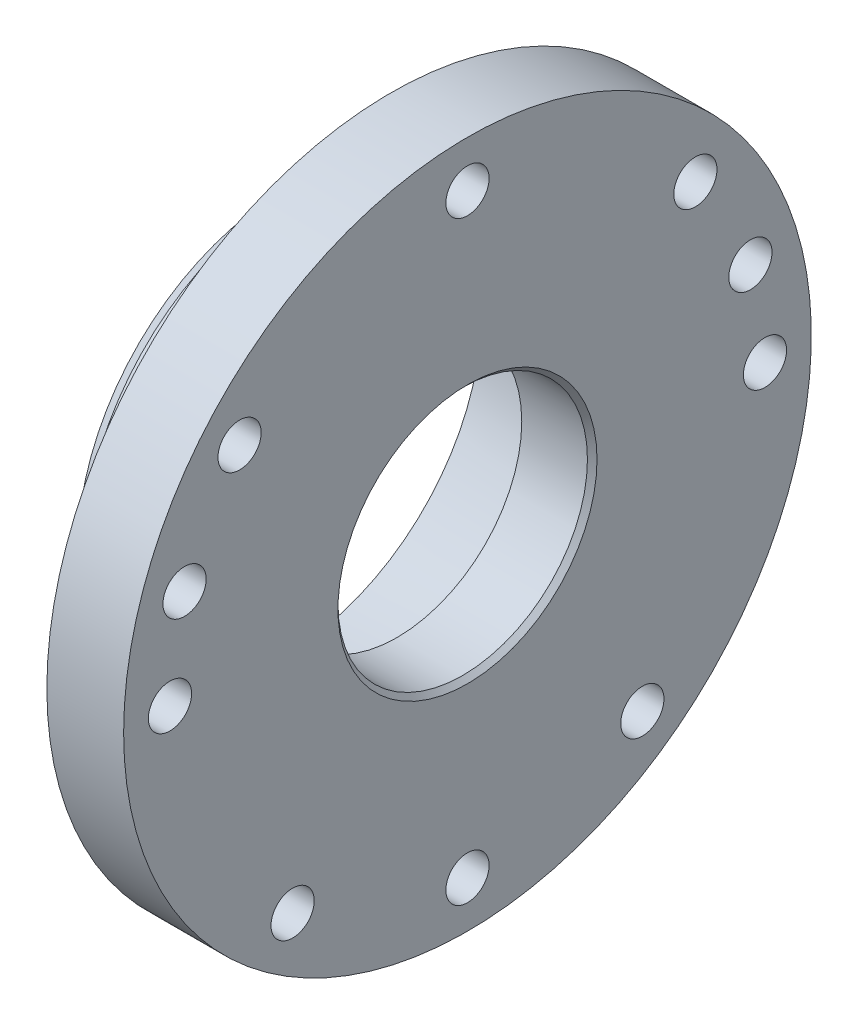
SolidWorks part; units mm, degrees
material "CD4Mc-U Duplex Stainless Steel"
ref_plane "Front Plane" through (0, 0, 0) normal (0, 0, 1) x (1, 0, 0)
ref_plane "Top Plane" through (0, 0, 0) normal (0, 1, 0) x (1, 0, 0)
ref_plane "Right Plane" through (0, 0, 0) normal (1, 0, 0) x (0, 0, -1)
sketch "Sketch1" plane through (0, 0, 0) normal (0, 0, 1) x (1, 0, 0)
  line L0 (0, 0) -> (170.4703, 0) construction
  line L1 (0, 65.0875) -> (0, 70.0151)
  line L2 (0, 70.0151) -> (35.1028, 70.0151)
  line L3 (35.1028, 70.0151) -> (35.1028, 113.7666)
  line L4 (35.1028, 113.7666) -> (60.5028, 113.7666)
  line L5 (60.5028, 113.7666) -> (60.5028, 41.275)
  line L6 (60.5028, 41.275) -> (37.1856, 41.275)
  line L7 (37.1856, 41.275) -> (37.1856, 54.8517)
  line L9 (0, 65.0875) -> (30.2297, 62.4427)
  line L10 (0, 65.0875) -> (23.1126, 65.0875) construction
  arc A2 (37.1856, 54.8517) -> (30.2297, 62.4427) centre (29.5656, 54.8517) ccw
  dimension "D8" = 15.24
  dimension "D9" = 65.0875
  dimension "D1" = 60.5028
  dimension "D2" = 113.7666
  dimension "D3" = 25.4
  dimension "D4" = 70.0151
  dimension "D5" = 5
  dimension "D6" = 41.275
  dimension "D7" = 23.3172
revolve "Revolve1" add sketch "Sketch1" angle 360 about L0
chamfer "Chamfer2" distance 1.5875 angle 45 1 edges at (60.5028, 0, 41.275)
sketch "Sketch3" plane through (35.1028, 0, 0) normal (-1, 0, 0) x (0, 0, 1)
  line L0 (0, 0) -> (0, 98.425) construction
  circle A0 centre (0, 0) radius 98.425 construction
  circle A1 centre (0, 98.425) radius 7.1501
  dimension "D1" = 196.85
  dimension "D2" = 14.3002
extrude "Cut-Extrude1" cut sketch "Sketch3" against normal through all
pattern_circular "CirPattern1" count 5 over 360 about axis through (0, 0, 0) along (1, 0, 0) of "Cut-Extrude1"
fillet "Fillet1" radius 0.762 1 edges at (35.1028, 0, 70.0151)
chamfer "Chamfer3" distance 3.175 distance2 1.5875 1 edges at (0, 0, 70.0151)
sketch "Sketch4" plane through (35.1028, 0, 0) normal (-1, 0, 0) x (0, 0, 1)
  line L0 (0, 0) -> (-98.425, 0) construction
  circle A0 centre (0, 0) radius 98.425 construction
  circle A1 centre (-98.425, 0) radius 7.1501
  dimension "D1" = 196.85
  dimension "D2" = 14.3002
extrude "Cut-Extrude2" cut sketch "Sketch4" against normal through all
mirror "Mirror1" about plane through (0, 0, 0) normal (0, 0, 1) of "Cut-Extrude2"
sketch "Sketch5" plane through (35.1028, 0, 0) normal (-1, 0, 0) x (0, 0, 1)
  line L0 (0, 0) -> (0, -98.425) construction
  circle A0 centre (0, 0) radius 98.425 construction
  circle A1 centre (0, -98.425) radius 7.1501
  dimension "D1" = 196.85
  dimension "D2" = 14.3002
extrude "Cut-Extrude3" cut sketch "Sketch5" against normal through all
pattern_circular "CirPattern2" count 36 over 360 about axis through (0, 0, 0) along (-1, 0, 0) skipping 1, 2, 3, 4, 5, 6, 7, 8, 9, 10, 11, 12, 14, 15, 16, 17, 18, 19, 20, 21, 22, 24, 25, 26, 27, 28, 29, 30, 31, 32, 33, 34, 35 of "Cut-Extrude3"
sketch "Sketch7" plane through (0, 0, 0) normal (0, 0, 1) x (1, 0, 0)
  line L0 (-34.0956, 0) -> (110.3274, 0) construction
  line L1 (20.8788, 70.0151) -> (20.8788, 67.1449)
  line L2 (34.3408, 70.0151) -> (3.175, 70.0151) construction
  line L3 (20.8788, 67.1449) -> (25.6794, 67.1449)
  line L4 (25.6794, 67.1449) -> (25.6794, 70.0151)
  line L5 (20.8788, 70.0151) -> (20.8788, 72.1748)
  line L6 (20.8788, 72.1748) -> (25.6794, 72.1748)
  line L7 (25.6794, 72.1748) -> (25.6794, 70.0151)
  line L8 (35.1028, 113.7666) -> (35.1028, -113.7666) construction
  dimension "D1" = 14.224
  dimension "D2" = 4.8006
  dimension "D3" = 2.8702
revolve "Cut-Revolve1" cut sketch "Sketch7" angle 360 about L0
sketch "Sketch8" plane through (0, 0, 0) normal (0, 1, 0) x (1, 0, 0)
  line L1 (0, -7.9375) -> (12.7, -7.9375)
  line L2 (0, -7.9375) -> (0, 7.9375)
  line L3 (0, 7.9375) -> (12.7, 7.9375)
  line L4 (12.7, -7.9375) -> (12.7, 7.9375)
  line L5 (0, -7.9375) -> (12.7, 7.9375) construction
  line L6 (0, 7.9375) -> (12.7, -7.9375) construction
  line L7 (0, 68.4276) -> (0, -68.4276) construction
  line L8 (20.8788, 0) -> (3.175, 0) construction
  point P6 (6.35, 0)
  dimension "D1" = 12.7
  dimension "D2" = 15.875
extrude "Cut-Extrude4" cut sketch "Sketch8" against normal through all
